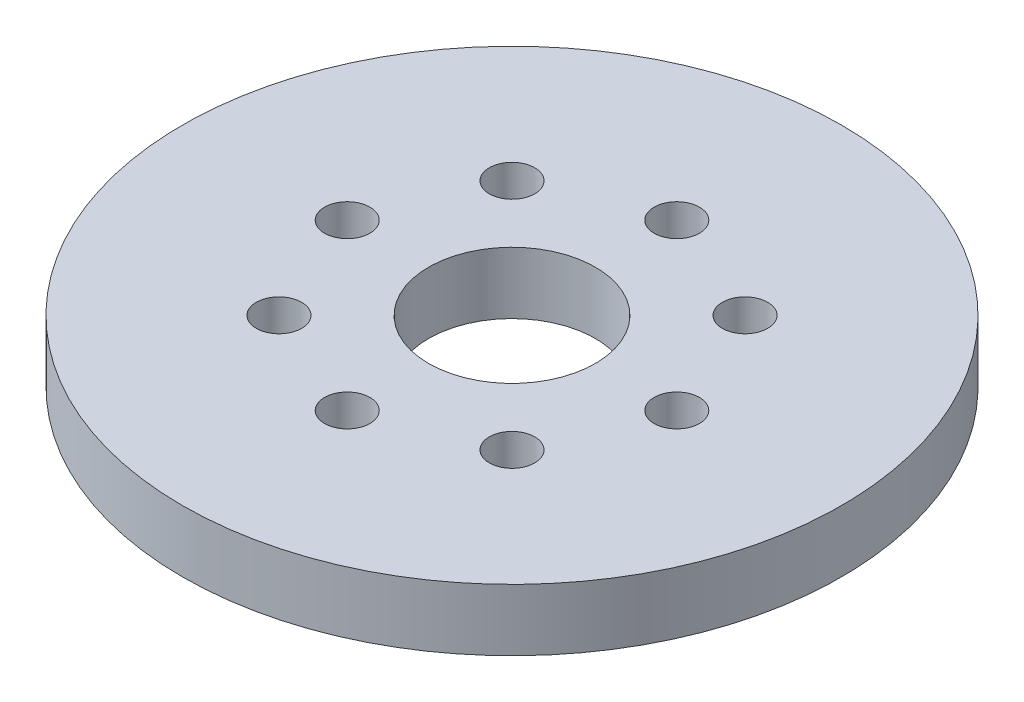
SolidWorks part; units mm, degrees
material "ABS PC"
ref_plane "Front Plane" through (0, 0, 0) normal (0, 0, 1) x (1, 0, 0)
ref_plane "Top Plane" through (0, 0, 0) normal (0, 1, 0) x (1, 0, 0)
ref_plane "Right Plane" through (0, 0, 0) normal (1, 0, 0) x (0, 0, -1)
sketch "Sketch1" plane through (0, 0, 0) normal (0, 1, 0) x (1, 0, 0)
  circle A1 centre (0, 0) radius 4.05
  circle A2 centre (0, 0) radius 16
  circle A3 centre (0, 8) radius 1.1
  circle A4 centre (5.6569, 5.6569) radius 1.1
  circle A5 centre (8, 0) radius 1.1
  circle A6 centre (5.6569, -5.6569) radius 1.1
  circle A7 centre (0, -8) radius 1.1
  circle A8 centre (-5.6569, -5.6569) radius 1.1
  circle A9 centre (-8, 0) radius 1.1
  circle A10 centre (-5.6569, 5.6569) radius 1.1
  dimension "D1" = 8
  dimension "D3" = 8.1
  dimension "D4" = 2.2
extrude "Boss-Extrude1" add sketch "Sketch1" along normal blind 3
